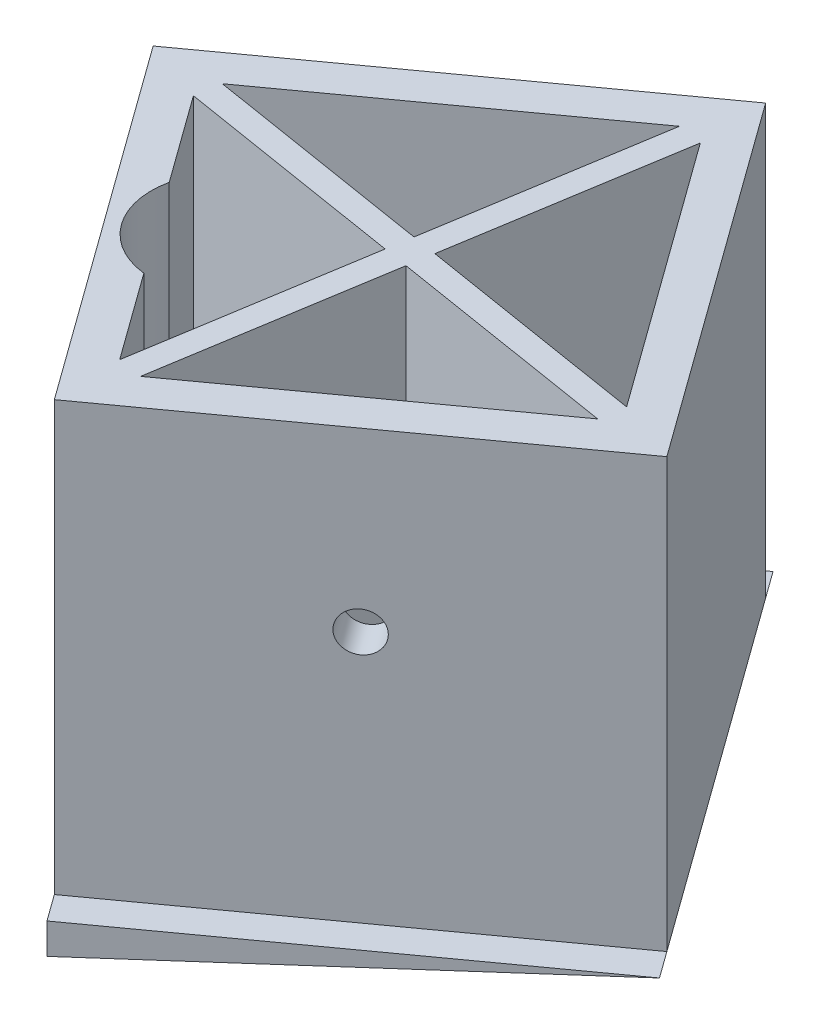
SolidWorks part; units mm, degrees
ref_plane "Front Plane" through (0, 0, 0) normal (0, 0, 1) x (1, 0, 0)
ref_plane "Top Plane" through (0, 0, 0) normal (0, 1, 0) x (1, 0, 0)
ref_plane "Right Plane" through (0, 0, 0) normal (1, 0, 0) x (0, 0, -1)
sketch "Sketch1" plane through (0, 0, 0) normal (0, 1, 0) x (1, 0, 0)
  line L0 (0, 82.55) -> (0, -82.55) construction
  line L1 (-107.95, 82.55) -> (107.95, 82.55) construction
  line L2 (-114.3, -82.55) -> (114.3, -82.55) construction
  line L3 (-124.3737, -76.1961) -> (-111.4355, -94.1105)
  line L4 (-111.4355, -94.1105) -> (-93.5211, -81.1723)
  line L5 (-93.5211, -81.1723) -> (-106.4593, -63.2579)
  line L6 (-106.4593, -63.2579) -> (-124.3737, -76.1961)
  line L7 (-114.3, -82.55) -> (-119.6867, -86.4404) construction
  line L8 (-105.0715, -106.6767) -> (-134.3018, -66.204) construction
  line L9 (-106.0875, -60.9529) -> (-126.6787, -75.8243) construction
  line L10 (-126.6787, -75.8243) -> (-111.8073, -96.4156) construction
  line L11 (-111.8073, -96.4156) -> (-91.216, -81.5441) construction
  line L12 (-91.216, -81.5441) -> (-106.0875, -60.9529) construction
  circle A0 centre (0, 0) radius 147.6375 construction
  circle A1 centre (-107.95, 82.55) radius 1.5
  circle A2 centre (107.95, 82.55) radius 1.5
  circle A3 centre (114.3, -82.55) radius 1.5
  circle A4 centre (-114.3, -82.55) radius 1.5
  dimension "D1" = 295.275
  dimension "D5" = 3
  dimension "D2" = 215.9
  dimension "D3" = 228.6
  dimension "D4" = 165.1
  dimension "D6" = 22.098
  dimension "D7" = 25.4
extrude "Boss-Extrude2" add sketch "Sketch1" along normal blind 2.54 contours L5 L6 L3 L4 A4
sketch "Sketch2" plane through (0, 2.54, 0) normal (0, 1, 0) x (1, 0, 0)
  line L0 (-106.8883, -65.9176) -> (-121.714, -76.6251)
  line L1 (-121.714, -76.6251) -> (-118.0222, -81.7368)
  line L2 (-111.0065, -91.4508) -> (-96.1808, -80.7433)
  line L3 (-96.1808, -80.7433) -> (-106.8883, -65.9176)
  line L4 (-124.3737, -76.1961) -> (-111.4355, -94.1105) construction
  line L5 (-93.5211, -81.1723) -> (-106.4593, -63.2579) construction
  line L6 (-106.4593, -63.2579) -> (-124.3737, -76.1961) construction
  line L7 (-111.4355, -94.1105) -> (-93.5211, -81.1723) construction
  line L8 (-106.4593, -63.2579) -> (-124.3737, -76.1961)
  line L9 (-124.3737, -76.1961) -> (-111.4355, -94.1105)
  line L10 (-111.4355, -94.1105) -> (-93.5211, -81.1723)
  line L11 (-93.5211, -81.1723) -> (-106.4593, -63.2579)
  line L12 (-114.6983, -86.3391) -> (-111.0065, -91.4508)
  line L13 (-121.714, -76.6251) -> (-111.0065, -91.4508) construction
  arc A0 (-118.0222, -81.7368) -> (-114.6983, -86.3391) centre (-114.3, -82.55) ccw
  dimension "D3" = 7.62
  dimension "D2" = 1.905
extrude "Boss-Extrude3" add sketch "Sketch2" along normal blind 19.05
sketch "Sketch3" plane through (0, 21.59, 0) normal (0, 1, 0) x (1, 0, 0)
  line L0 (-124.3737, -76.1961) -> (-93.5211, -81.1723) construction
  line L1 (-106.4593, -63.2579) -> (-111.4355, -94.1105) construction
  line L2 (-111.4355, -94.1105) -> (-93.5211, -81.1723) construction
  line L3 (-124.4748, -76.823) -> (-93.6222, -81.7992)
  line L4 (-107.0862, -63.1568) -> (-112.0624, -94.0094)
  line L5 (-124.2726, -75.5692) -> (-93.42, -80.5454)
  line L6 (-105.8324, -63.3591) -> (-110.8086, -94.2116)
  dimension "D1" = 0.635
extrude "Boss-Extrude6" add sketch "Sketch3" against normal up to surface (19.05 mm away) up to face at (-111.5897, 2.54, 80.5926)
sketch "Sketch4" plane through (6.4691, 0, 8.9572) normal (0.5855, 0, 0.8107) x (0.8107, 0, -0.5855)
  line L0 (-134.3902, 0) -> (-134.3902, 12.7) construction
  line L2 (-145.4392, 0) -> (-123.3412, 0) construction
  circle A0 centre (-134.3902, 12.7) radius 1
  dimension "D2" = 2
  dimension "D1" = 12.7
extrude "Cut-Extrude1" cut sketch "Sketch4" against normal through all
fillet "Fillet1" radius 6.35 2 edges at (-114.3011, 2.54, 71.2714) (-103.5937, 2.54, 86.0971)
ref_plane "Plane1" through (0, 0, 0) normal (-0.5855, 0, -0.8107) x (-0.8107, 0, 0.5855)
sketch "Sketch5" plane through (0, 0, 0) normal (-0.5855, 0, -0.8107) x (-0.8107, 0, 0.5855)
  line L0 (123.3412, 0) -> (145.4392, 0)
  line L1 (145.4392, 0) -> (145.4392, -1.5452)
  line L2 (145.4392, -1.5452) -> (123.3412, 0)
  dimension "D1" = 4
extrude "Boss-Extrude7" add sketch "Sketch5" along normal mid plane 25.4
sketch "Sketch6" plane through (0, 2.54, 0) normal (0, 1, 0) x (1, 0, 0)
  circle A0 centre (-114.3, -82.55) radius 1.5 construction
  circle A1 centre (-114.3, -82.55) radius 1.5
extrude "Cut-Extrude2" cut sketch "Sketch6" against normal through all
